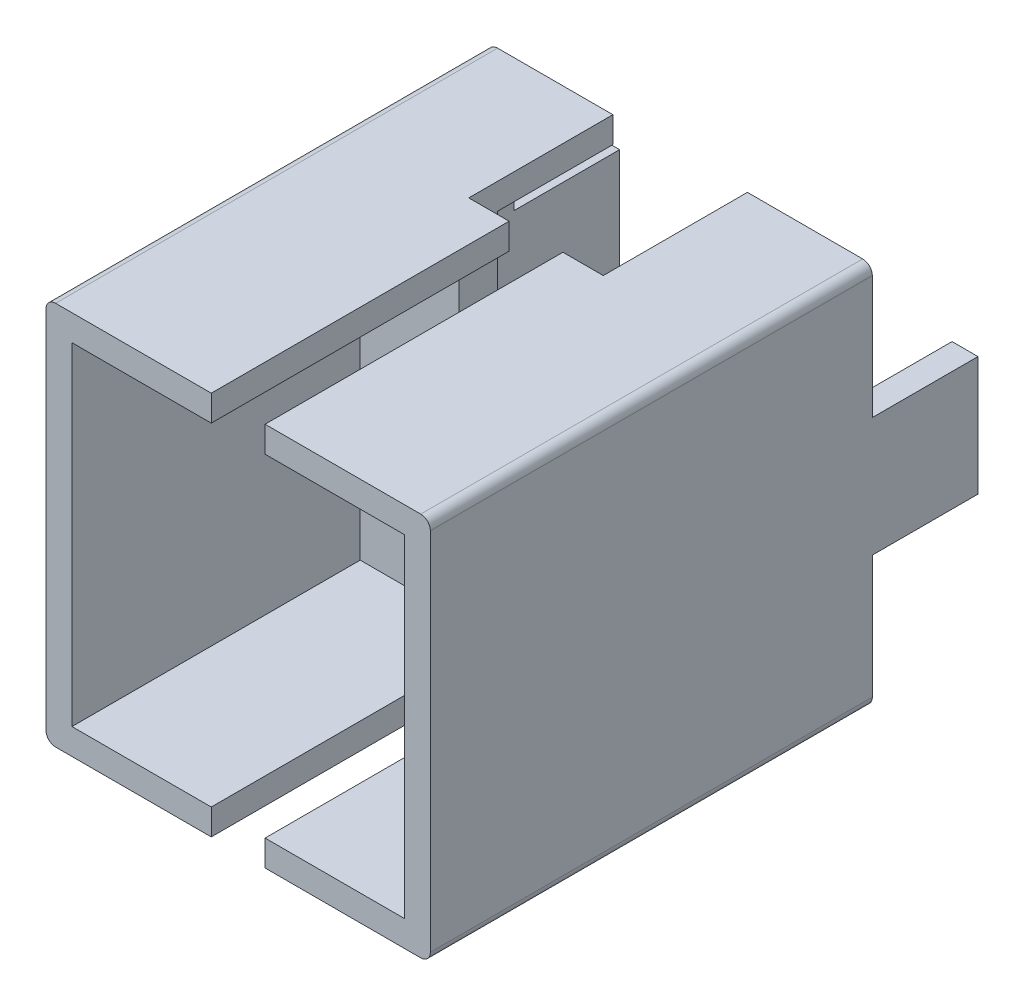
SolidWorks part; units mm, degrees
ref_plane "Front Plane" through (0, 0, 0) normal (0, 0, 1) x (1, 0, 0)
ref_plane "Top Plane" through (0, 0, 0) normal (0, 1, 0) x (1, 0, 0)
ref_plane "Right Plane" through (0, 0, 0) normal (1, 0, 0) x (0, 0, -1)
sketch "Sketch1" plane through (0, 0, 0) normal (0, 0, 1) x (1, 0, 0)
  line L0 (-8.65, 8.65) -> (-1.4, 8.65)
  line L1 (-10, -10) -> (-1.4, -10)
  line L2 (-10, -10) -> (-10, 10)
  line L3 (-10, 10) -> (-1.4, 10)
  line L4 (10, -10) -> (10, 10)
  line L5 (-10, -10) -> (10, 10) construction
  line L6 (-10, 10) -> (10, -10) construction
  line L7 (8.65, -8.65) -> (8.65, 8.65)
  line L8 (-8.65, -8.65) -> (-1.4, -8.65)
  line L9 (-8.65, -8.65) -> (-8.65, 8.65)
  line L10 (0, 0) -> (0, 10) construction
  line L11 (0, 0) -> (0, -10) construction
  line L14 (-1.4, 8.65) -> (-1.4, 10)
  line L19 (1.4, 10) -> (10, 10)
  line L20 (-10, 10) -> (10, 10) construction
  line L21 (1.4, 8.65) -> (8.65, 8.65)
  line L22 (-8.65, 8.65) -> (8.65, 8.65) construction
  line L26 (1.4, -10) -> (10, -10)
  line L27 (-10, -10) -> (10, -10) construction
  line L28 (1.4, -8.65) -> (8.65, -8.65)
  line L29 (-8.65, -8.65) -> (8.65, -8.65) construction
  line L30 (-1.4, -8.65) -> (-1.4, -10)
  line L31 (1.4, -8.65) -> (1.4, -10)
  line L32 (1.4, 8.65) -> (1.4, 10)
  point P0 (0, 0)
  dimension "D1" = 20
  dimension "D2" = 20
  dimension "D3" = 1.35
extrude "Boss-Extrude1" add sketch "Sketch1" against normal blind 23
sketch "Sketch2" plane through (0, -10, 0) normal (0, -1, 0) x (1, 0, 0)
  line L0 (1.4, -23) -> (-1.4, -23) construction
  line L1 (0, -23) -> (0, -15.5) construction
  line L2 (-3.5, -15.5) -> (3.5, -15.5)
  line L3 (3.5, -15.5) -> (3.5, -23)
  line L4 (1.4, -23) -> (10, -23) construction
  line L5 (3.5, -23) -> (-3.5, -23)
  line L6 (-3.5, -15.5) -> (-3.5, -23)
extrude "Cut-Extrude1" cut sketch "Sketch2" against normal blind 22
sketch "Sketch3" plane through (0, 0, -15.5) normal (0, 0, -1) x (-1, 0, 0)
  line L0 (3.5, 8.65) -> (3.5, 10) construction
  line L1 (8.65, 8.65) -> (3.5, 8.65)
  line L2 (8.65, 8.65) -> (8.65, -8.65)
  line L3 (8.65, -8.65) -> (3.5, -8.65)
  line L4 (-8.65, 8.65) -> (-8.65, -8.65)
  line L5 (3.5, -8.65) -> (3.5, -5)
  line L6 (-3.5, 8.65) -> (-3.5, 5)
  line L7 (-3.5, 5) -> (3.5, 5)
  line L8 (3.5, 8.65) -> (3.5, 5)
  line L9 (-1.4, 10) -> (-3.5, 10) construction
  line L10 (0, 0) -> (-2.584, 0) construction
  line L11 (-3.5, 8.65) -> (-8.65, 8.65)
  line L12 (-3.5, -5) -> (3.5, -5)
  line L13 (-3.5, -8.65) -> (-3.5, -5)
  line L14 (-3.5, -8.65) -> (-8.65, -8.65)
  dimension "D1" = 5
extrude "Boss-Extrude2" add sketch "Sketch3" along normal blind 1.5 and the other way blind 0.5
fillet "Fillet1" radius 0.5 4 edges at (-10, -10, -11.5) (-10, 10, -11.5) (10, -10, -11.5) (10, 10, -11.5)
sketch "Sketch4" plane through (0, 0, -17) normal (0, 0, -1) x (-1, 0, 0)
  circle A0 centre (0, 0) radius 3.5
  circle A1 centre (0, 0) radius 2.5
  dimension "D1" = 1
extrude "Boss-Extrude3" add sketch "Sketch4" along normal blind 5.5
sketch "Sketch5" plane through (0, 0, -23) normal (0, 0, -1) x (-1, 0, 0)
  line L1 (0, 0) -> (0, -1.7226) construction
  line L2 (-8.65, -3.1) -> (-8.65, 3.1)
  line L3 (-8.65, 3.1) -> (-10, 3.1)
  line L4 (-10, -3.1) -> (-10, 3.1)
  line L5 (-10, -9.5) -> (-10, 9.5) construction
  line L6 (-8.65, -3.1) -> (-10, -3.1)
  line L7 (8.65, -3.1) -> (10, -3.1)
  line L8 (10, -3.1) -> (10, 3.1)
  line L9 (8.65, 3.1) -> (10, 3.1)
  line L10 (8.65, -3.1) -> (8.65, 3.1)
extrude "Boss-Extrude4" add sketch "Sketch5" along normal blind 5.5
